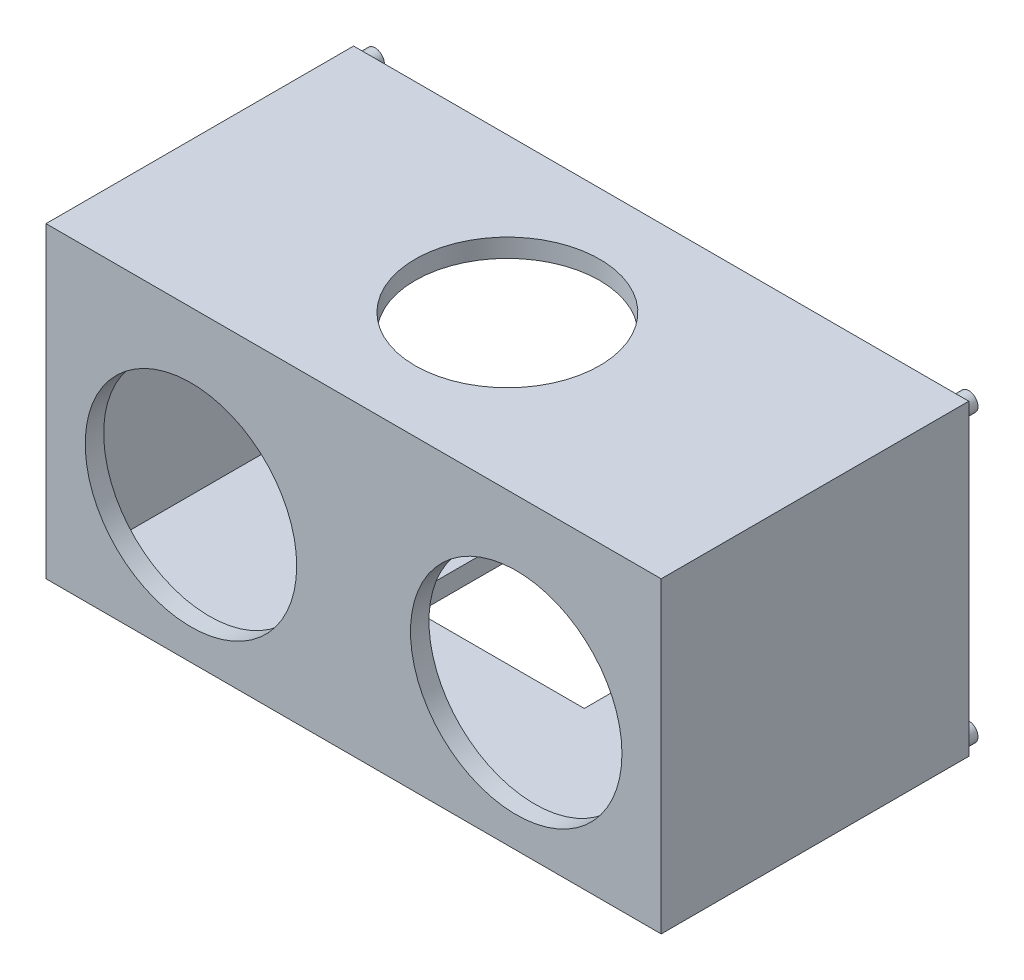
SolidWorks part; units mm, degrees
ref_plane "Front Plane" through (0, 0, 0) normal (0, 0, 1) x (1, 0, 0)
ref_plane "Top Plane" through (0, 0, 0) normal (0, 1, 0) x (1, 0, 0)
ref_plane "Right Plane" through (0, 0, 0) normal (1, 0, 0) x (0, 0, -1)
sketch "Sketch1" plane through (0, 0, 0) normal (0, 0, 1) x (1, 0, 0)
  line L1 (-25.4, 12.7) -> (25.4, 12.7)
  line L2 (-25.4, 12.7) -> (-25.4, -12.7)
  line L3 (-25.4, -12.7) -> (25.4, -12.7)
  line L4 (25.4, 12.7) -> (25.4, -12.7)
  dimension "D1" = 50.8
  dimension "D2" = 25.4
  dimension "D3" = 25.4
  dimension "D4" = 12.7
extrude "Boss-Extrude1" add sketch "Sketch1" along normal blind 25.4
shell "Shell1" thickness 1.524
sketch "Sketch2" plane through (0, 0, 0) normal (0, 0, -1) x (-1, 0, 0)
  line L0 (-25.4, 12.7) -> (25.4, 12.7) construction
  line L1 (-25.4, -12.7) -> (-25.4, 12.7) construction
  line L3 (0, -15.0373) -> (0, 13.9007) construction
  line L4 (-29.55, 0) -> (27.6266, 0) construction
  circle A0 centre (-24.511, 11.811) radius 0.762
  circle A2 centre (24.511, 11.811) radius 0.762
  circle A3 centre (24.511, -11.811) radius 0.762
  circle A4 centre (-24.511, -11.811) radius 0.762
  dimension "D1" = 1.524
  dimension "D2" = 0.889
  dimension "D3" = 0.889
extrude "Boss-Extrude2" add sketch "Sketch2" along normal blind 0.889
sketch "Sketch3" plane through (0, -12.7, 0) normal (0, -1, 0) x (-1, 0, 0)
  line L8 (7.62, -13.97) -> (-7.62, -13.97)
  line L9 (7.62, -13.97) -> (7.62, 0)
  line L10 (7.62, 0) -> (-7.62, 0)
  line L11 (-7.62, -13.97) -> (-7.62, 0)
  line L12 (-25.4, -25.4) -> (-25.4, 0) construction
  line L13 (25.4, -25.4) -> (25.4, 0) construction
  line L14 (25.4, 0) -> (-25.4, 0) construction
  line L15 (25.4, -25.4) -> (-25.4, -25.4) construction
  dimension "D1" = 17.78
  dimension "D2" = 17.78
  dimension "D3" = 0
  dimension "D4" = 11.43
extrude "Cut-Extrude1" cut sketch "Sketch3" against normal up to surface (23.876 mm away) contours L11 L10 L9 L8 up to face at (0, 11.176, 11.938)
sketch "Sketch4" plane through (0, 12.7, 0) normal (0, 1, 0) x (1, 0, 0)
  line L0 (25.4, -25.4) -> (25.4, 0) construction
  line L2 (25.4, -25.4) -> (-25.4, -25.4) construction
  circle A0 centre (0, -12.7) radius 7.62
  dimension "D1" = 15.24
  dimension "D2" = 25.4
  dimension "D3" = 12.7
extrude "Cut-Extrude2" cut sketch "Sketch4" against normal up to surface (23.876 mm away) up to face at (0, -11.176, 9.4615)
sketch "Sketch5" plane through (0, 0, 25.4) normal (0, 0, 1) x (1, 0, 0)
  line L0 (0, -15.7675) -> (0, 14.8915) construction
  line L1 (-25.4, -12.7) -> (25.4, -12.7) construction
  line L3 (-25.4, 12.7) -> (-25.4, -12.7) construction
  line L4 (25.4, -12.7) -> (25.4, 12.7) construction
  circle A0 centre (-13.4303, -1.4288) radius 8.7312
  circle A1 centre (13.4302, -1.4288) radius 8.7312
  point P9 (0, 0)
  dimension "D1" = 17.4625
  dimension "D2" = 17.4625
  dimension "D3" = 11.2712
  dimension "D4" = 11.9697
  dimension "D6" = 11.2712
  dimension "D5" = 11.9697
extrude "Cut-Extrude3" cut sketch "Sketch5" against normal through all and the other way through all
